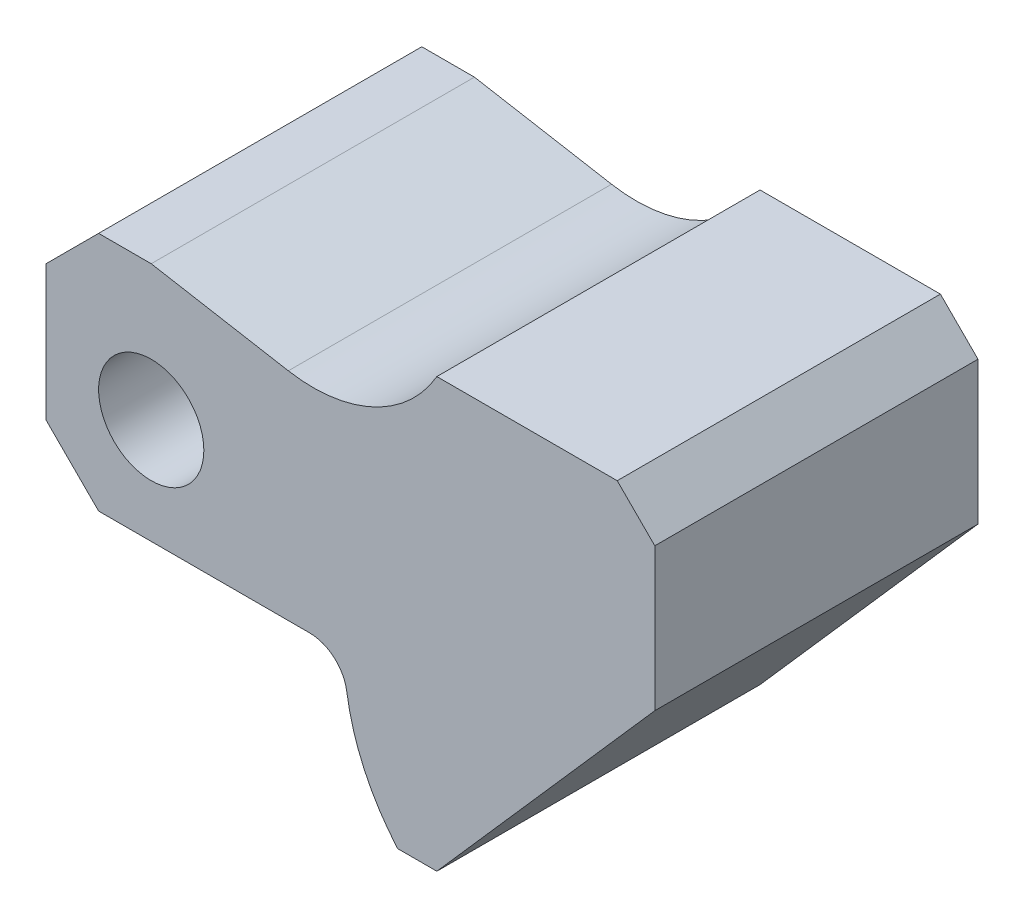
SolidWorks part; units mm, degrees
material "AISI 1020"
ref_plane "Plan de face" through (0, 0, 0) normal (0, 0, 1) x (1, 0, 0)
ref_plane "Plan de dessus" through (0, 0, 0) normal (0, 1, 0) x (1, 0, 0)
ref_plane "Plan de droite" through (0, 0, 0) normal (1, 0, 0) x (0, 0, -1)
sketch "Esquisse1" plane through (0, 0, 0) normal (0, 0, 1) x (1, 0, 0)
  line L0 (-14, 18) -> (0, 18)
  line L1 (67, -33) -> (-14, -33) construction
  line L2 (67, -33) -> (67, 24) construction
  line L3 (67, 24) -> (-14, 24) construction
  line L4 (-14, -33) -> (-14, 24) construction
  line L5 (0, 18) -> (18.2431, 14.7833)
  line L6 (38, 24) -> (62, 24)
  line L7 (62, 24) -> (67, 24)
  line L8 (67, 24) -> (67, 0)
  line L9 (67, 0) -> (38, -33)
  line L10 (38, -33) -> (32.7881, -33)
  line L12 (21.0666, -14) -> (-14, -14)
  line L13 (-14, -14) -> (-14, 18)
  circle A0 centre (0, 0) radius 7
  arc A1 (18.2431, 14.7833) -> (38, 24) centre (21.5424, 33.4946) ccw
  arc A2 (32.7881, -33) -> (26.0123, -18.2647) centre (54.697, -14) cw
  arc A3 (26.0123, -18.2647) -> (21.0666, -14) centre (21.0666, -19) ccw
  point P18 (32.4447, -33)
  point P22 (32.7442, -33)
  point P23 (37.9623, -4)
  point P25 (67, 23.367)
  dimension "D7" = 32
  dimension "D13" = 5
  dimension "D14" = 29
  dimension "D9" = 19
  dimension "D18" = 14
  dimension "D1" = 81
  dimension "D2" = 57
  dimension "D3" = 29
  dimension "D4" = 24
  dimension "D5" = 14
  dimension "D6" = 14
  dimension "D8" = 19
  dimension "D12" = 10
  dimension "D15" = 29
  dimension "D16" = 14
  dimension "D17" = 19
extrude "Boss.-Extru.1" add sketch "Esquisse1" along normal blind 43
chamfer "Chanfrein1" distance 7 angle 45 2 edges at (-14, -14, 21.5) (-14, 18, 21.5)
chamfer "Chanfrein2" distance 5 angle 45 1 edges at (67, 24, 21.5)
equation "\"A\"= 81"
equation "\"B\"= 57"
equation "\"C\"= 43"
equation "\"D1@Boss.-Extru.1\"=\"C\""
